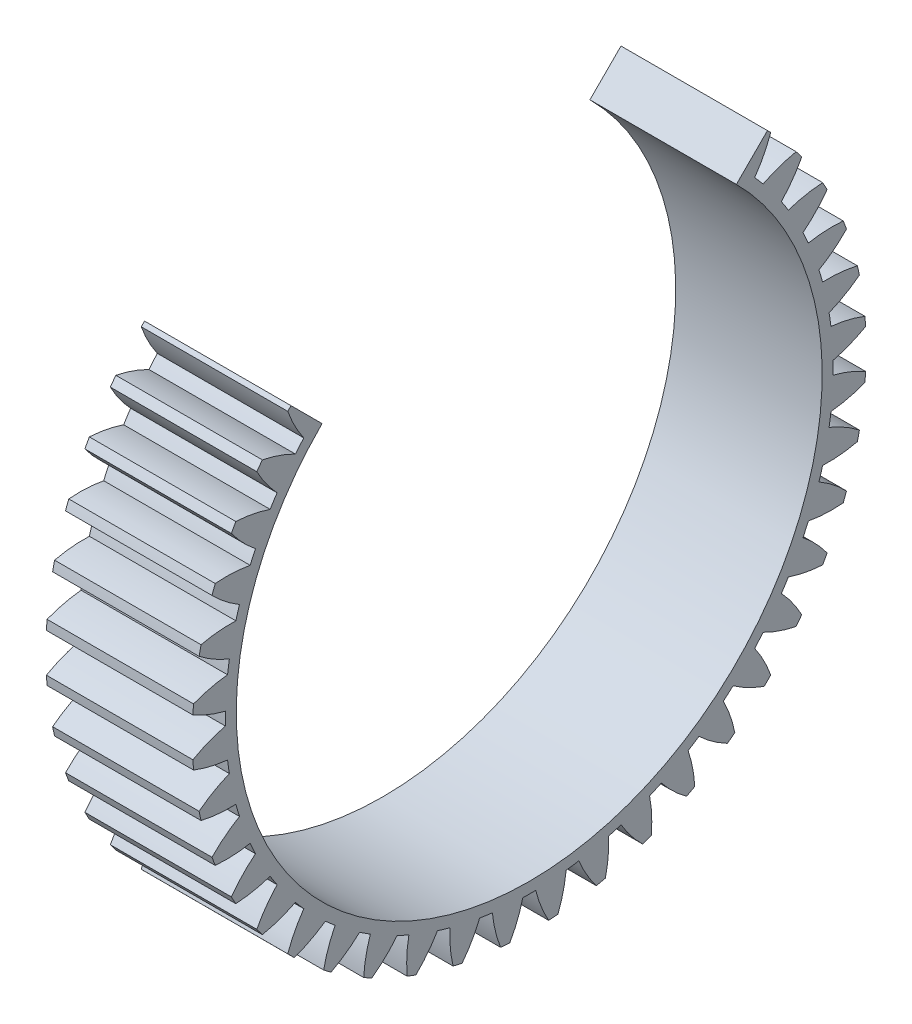
SolidWorks part; units mm, degrees
ref_plane "Plane1" through (0, 0, 0) normal (0, 0, 1) x (1, 0, 0)
ref_plane "Plane2" through (0, 0, 0) normal (0, 1, 0) x (1, 0, 0)
ref_plane "Plane3" through (0, 0, 0) normal (1, 0, 0) x (0, 0, -1)
other "Configuration Table"
sketch "HoldingSke" plane through (0, 0, 0) normal (0, 1, 0) x (1, 0, 0)
  line L0 (0, 0) -> (0.4796, -0.4631)
  line L1 (-15, 0) -> (100, 0) construction
  line L2 (0, 0) -> (-2.1039, 2.3779)
  line L3 (0, 0) -> (-11.863, 4.5341)
  line L4 (0, 0) -> (6.2122, 5.9991)
  line L5 (0, 0) -> (-46.8476, -17.4728)
  line L6 (0, 0) -> (-8.2896, -5.593)
  line L7 (-2.1039, 2.3779) -> (8.6586, 51.2059)
  line L8 (-76.2, 54.61) -> (-71.8, 54.61)
  line L9 (-71.009, 38.7566) -> (-53.1078, 45.2721)
  line L10 (-76.2, 71.12) -> (104.1128, 71.12)
  line L11 (0, 0) -> (-10, 0)
  line L12 (-76.2, 101.6) -> (-76.147, 101.6)
  line L13 (24.9733, 27.94) -> (52.9518, 28.4284)
  line L14 (24.9733, 27.94) -> (24.9743, 27.94)
  line L15 (24.9733, 27.94) -> (100.4006, 29.5858)
  line L16 (-63.627, -1.5) -> (-12.827, -1.5)
  circle A0 centre (0, 0) radius 30
  circle A1 centre (0, 0) radius 31.124
  circle A2 centre (0, 0) radius 37.5
  circle A3 centre (0, 0) radius 30
  dimension "MHD" = 62.248
  dimension "Hub_dia" = 75
  dimension "Bore" = 60
  dimension "MBD" = 60
  dimension "Num_teeth" = 44
  dimension "Pitch" = 0.6667
  dimension "Overall_len" = 50
  dimension "Show_teeth" = 44
  dimension "Thickness" = 10
  dimension "OAL" = 50.0001
  dimension "T_dim" = 4.4
  dimension "Ap" = 20
  dimension "H" = 19.05
  dimension "Pitch_radius" = 180.3128
  dimension "Width" = 10
  dimension "Backlash" = 0.053
  dimension "Addendum_fac" = 1
  dimension "Dedendum_fac" = 1.25
  dimension "Clearance_fac" = 0.25
  dimension "Dedendum_add" = 0.001
  dimension "Module" = 1.5
sketch "BasProSke" plane through (0, 0, 0) normal (0, 1, 0) x (1, 0, 0)
  line L0 (-10, 0) -> (60, 0) construction
  line L1 (0, 0) -> (0, 34.5)
  line L2 (0, 0) -> (15, 0)
  line L3 (15, 0) -> (15, 34.5)
  line L4 (15, 34.5) -> (0, 34.5)
  dimension "Thickness" = 15
  dimension "Diameter" = 69
revolve "Base-Revolve" add sketch "BasProSke" angle 360 about L0
sketch "TooCutSke" plane through (0, 0, 0) normal (1, 0, 0) x (0, 0, -1)
  line L1 (0, 0) -> (0, 107) construction
  line L2 (0, 0) -> (-1.2706, 32.9755) construction
  line L3 (0, 0) -> (-4.7058, 65.7962) construction
  line L4 (-1.2706, 32.9755) -> (-2.3529, 32.8981) construction
  arc A0 (0.6591, 31.117) -> (-0.6591, 31.117) centre (0, 0) ccw
  arc A1 (2.0005, 34.4674) -> (-2.0005, 34.4674) centre (0, 0) ccw
  circle A2 centre (0, 0) radius 33 construction
  circle A3 centre (0, 0) radius 31.0099 construction
  arc A4 (-0.6591, 31.117) -> (-2.0005, 34.4674) centre (-13.4691, 27.932) ccw
  arc A5 (2.0005, 34.4674) -> (0.6591, 31.117) centre (13.4691, 27.932) ccw
  dimension "Root_dia" = 62.248
  dimension "Overcut_dia" = 69.0508
  dimension "Pitch_dia" = 66
  dimension "Base_dia" = 62.0197
  dimension "Flank_rad" = 13.2
  dimension "Half_ang" = 4.091
  dimension "Half_CT" = 1.0851
extrude "ToothCut" cut sketch "TooCutSke" along normal through all
fillet "Breaks" [suppressed] radius 0.03
fillet "RootFillets" [suppressed] radius 0.376
pattern_circular "TeethCuts" count 44 every 8.182 about axis through (-10, 0, 0) along (1, 0, 0) of "ToothCut", "RootFillets", "Breaks"
sketch "HubNeaOneSke" plane through (0, 0, 0) normal (-1, 0, 0) x (0, 0, 1)
  circle A0 centre (0, 0) radius 31.124
  dimension "Diameter" = 62.248
extrude "HubNearOne" [suppressed] add sketch "HubNeaOneSke" along normal blind 35.0001
sketch "HubNeaBotSke" plane through (0, 0, 0) normal (-1, 0, 0) x (0, 0, 1)
  circle A0 centre (0, 0) radius 31.124
  dimension "Diameter" = 62.248
extrude "HubNearBoth" [suppressed] add sketch "HubNeaBotSke" along normal blind 17.5
ref_plane "FarPln" through (15, 0, 0) normal (1, 0, 0) x (0, 0, -1)
sketch "HubFarSke" plane through (15, 0, 0) normal (1, 0, 0) x (0, 0, -1)
  circle A0 centre (0, 0) radius 31.124
  dimension "Diameter" = 62.248
extrude "HubFar" [suppressed] add sketch "HubFarSke" along normal blind 17.5
sketch "BorSke" plane through (0, 0, 0) normal (1, 0, 0) x (0, 0, -1)
  circle A0 centre (0, 0) radius 30
  dimension "Diameter" = 60
extrude "Bore" cut sketch "BorSke" along normal mid plane 100.0001
sketch "KeySke" plane through (0, 0, 0) normal (1, 0, 0) x (0, 0, -1)
  line L0 (-9, 0) -> (-9, 34.4)
  line L1 (-9, 34.4) -> (9, 34.4)
  line L2 (9, 34.4) -> (9, 0)
  line L3 (0, 0) -> (0, 34) construction
  line L4 (-9, 0) -> (9, 0)
  dimension "Offset" = 34.4
  dimension "Width" = 18
extrude "Keyway" [suppressed] cut sketch "KeySke" along normal mid plane 100.0001
pattern_circular "Keyway2" [suppressed] count 2 every 90 about axis through (-10, 0, 0) along (1, 0, 0)
sketch "Sketch1" plane through (15, 0, 0) normal (1, 0, 0) x (0, 0, -1)
  line L0 (-24.3952, 24.3952) -> (-21.2132, 21.2132)
  line L1 (-21.2132, 21.2132) -> (0, 0) construction
  line L2 (0, 0) -> (21.2132, 21.2132) construction
  line L3 (24.3952, 24.3952) -> (21.2132, 21.2132)
  line L4 (0, 0) -> (0, 34.5) construction
  arc A0 (-24.3952, 24.3952) -> (24.3952, 24.3952) centre (0, 0) cw
  arc A1 (-21.2132, 21.2132) -> (21.2132, 21.2132) centre (0, 0) cw
  circle A2 centre (0, 0) radius 30 construction
  arc A3 (-1.9865, 34.4428) -> (-2.9355, 34.3749) centre (0, 0) ccw construction
  point P11 (-2.4612, 34.4121)
  dimension "D1" = 45
  dimension "D2" = 45
extrude "Cut-Extrude1" cut sketch "Sketch1" against normal through all
equation "' \"Module@HoldingSke\" = 6.35"
equation "' \"Num_teeth@HoldingSke\" = 12"
equation "' \"Ap@HoldingSke\" =  20"
equation "' \"Ap@HoldingSke\" = 20"
equation "' \"Width@HoldingSke\" = 0.5 * 25.4"
equation "' \"Hub_dia@HoldingSke\"= 1 * 25.4"
equation "' \"Hub_dia@HoldingSke\" = 1 * 25.4"
equation "' \"Overall_len@HoldingSke\" = 1.0 * 25.4"
equation "' \"Bore@HoldingSke\" = 0.75 * 25.4"
equation "' \"T_dim@HoldingSke\" = 0.1 * 25.4"
equation "' \"Width@KeySke\" = 0.25 * 25.4"
equation "' \"Show_teeth@HoldingSke\" = 13"
equation "' \"Backlash@HoldingSke\" = 0.009 * 25.4"
equation "' \"Addendum_fac@HoldingSke\" = 1.0"
equation "' \"Dedendum_fac@HoldingSke\" = 1.25"
equation "' \"Dedendum_add@HoldingSke\" = 0.00005 * 25.4"
equation "' \"Clearance_fac@HoldingSke\" = 0.25"
equation "\"Pitch@HoldingSke\" = 1 / \"Module@HoldingSke\""
equation "\"Overcut_dia@TooCutSke\" = (\"Num_teeth@HoldingSke\" + 2 * \"Addendum_fac@HoldingSke\") / \"Pitch@HoldingSke\" + 0.002 * 25.4"
equation "\"Pitch_dia@TooCutSke\" = \"Num_teeth@HoldingSke\" / \"Pitch@HoldingSke\""
equation "\"Base_dia@TooCutSke\" = \"Num_teeth@HoldingSke\" / \"Pitch@HoldingSke\" * cos((\"Ap@HoldingSke\"  * 3.14159265 / 180))"
equation "\"Root_dia@TooCutSke\" = (\"Num_teeth@HoldingSke\" + 2) / \"Pitch@HoldingSke\" - 2 * (\"Addendum_fac@HoldingSke\" + \"Dedendum_fac@HoldingSke\") / \"Pitch@HoldingSke\" - \"Dedendum_add@HoldingSke\" * 2"
equation "\"Half_ang@TooCutSke\" = 180 / \"Num_teeth@HoldingSke\""
equation "\"Half_CT@TooCutSke\" = \"Num_teeth@HoldingSke\" / \"Pitch@HoldingSke\" * sin((3.14159265 / 2 / \"Num_teeth@HoldingSke\")) / 2 - 7 * \"Backlash@HoldingSke\" / 4"
equation "\"Flank_rad@TooCutSke\" = \"Num_teeth@HoldingSke\" / \"Pitch@HoldingSke\" / 5"
equation "\"Radius@RootFillets\" = \"Clearance_fac@HoldingSke\" / \"Pitch@HoldingSke\" + \"Dedendum_add@HoldingSke\""
equation "\"Break_rad@Breaks\" = 0.02 / \"Pitch@HoldingSke\""
equation "\"Thickness@HoldingSke\" = \"Width@HoldingSke\""
equation "\"OAL@HoldingSke\" = \"Thickness@HoldingSke\""
equation "\"MHD@HoldingSke\" = (\"Num_teeth@HoldingSke\" + 2) / \"Pitch@HoldingSke\" - 2 * (\"Addendum_fac@HoldingSke\" + \"Dedendum_fac@HoldingSke\")  / \"Pitch@HoldingSke\" - \"Dedendum_add@HoldingSke\" * 2"
equation "\"MBD@HoldingSke\" = (\"Num_teeth@HoldingSke\" + 2) / \"Pitch@HoldingSke\" - 2 * (\"Addendum_fac@HoldingSke\" + \"Dedendum_fac@HoldingSke\")  / \"Pitch@HoldingSke\" - \"Dedendum_add@HoldingSke\" * 2 - 0.002 * 25.4"
equation "\"MHD@HoldingSke\" = ((sgn( \"MHD@HoldingSke\" - \"Hub_dia@HoldingSke\" )-1)*( \"MHD@HoldingSke\" - \"Hub_dia@HoldingSke\" ))/-2+ \"Hub_dia@HoldingSke\""
equation "\"MBD@HoldingSke\" = ((sgn( \"MBD@HoldingSke\" - \"Bore@HoldingSke\" )-1)*( \"MBD@HoldingSke\" - \"Bore@HoldingSke\" ))/-2+ \"Bore@HoldingSke\""
equation "\"OAL@HoldingSke\" = ((sgn( \"OAL@HoldingSke\" - \"Overall_len@HoldingSke\" )+1)*( \"OAL@HoldingSke\" - \"Overall_len@HoldingSke\" ))/2 + \"Overall_len@HoldingSke\" + 0.000002 * 25.4"
equation "\"Num_teeth@TeethCuts\" = int( \"Show_teeth@HoldingSke\" ) + 1"
equation "\"Num_teeth@TeethCuts\" = ((sgn( \"Num_teeth@TeethCuts\" - \"Num_teeth@HoldingSke\" )-1)*( \"Num_teeth@TeethCuts\" - \"Num_teeth@HoldingSke\" ))/-2+ \"Num_teeth@HoldingSke\""
equation "\"Num_teeth@TeethCuts\" = ((sgn( \"Num_teeth@TeethCuts\" - 2.0)+1)*( \"Num_teeth@TeethCuts\" - 2.0))/2 +2.0"
equation "\"Angle@TeethCuts\" = 360.0 / \"Num_teeth@HoldingSke\""
equation "\"Diameter@BasProSke\" = (\"Num_teeth@HoldingSke\" + 2 * \"Addendum_fac@HoldingSke\") / \"Pitch@HoldingSke\""
equation "' \"Fillet_rad@BasProSke\" =  \"Thickness@HoldingSke\" * 0.05"
equation "' \"Fillet_rad@BasProSke\" = \"Thickness@HoldingSke\" * 0.05"
equation "\"MHD@HoldingSke\" = ((sgn( \"MHD@HoldingSke\" - \"Root_dia@TooCutSke\" )-1)*( \"MHD@HoldingSke\" - \"Root_dia@TooCutSke\" ))/-2+ \"Root_dia@TooCutSke\""
equation "\"Diameter@HubNeaOneSke\" = \"MHD@HoldingSke\""
equation "\"Length@HubNearOne\" = \"OAL@HoldingSke\" - \"Thickness@BasProSke\""
equation "\"Diameter@HubNeaBotSke\" = \"MHD@HoldingSke\""
equation "\"Length@HubNearBoth\" = ( \"OAL@HoldingSke\" - \"Thickness@BasProSke\" ) / 2.0"
equation "\"Thickness@FarPln\" = \"Thickness@BasProSke\""
equation "\"Diameter@HubFarSke\" = \"MHD@HoldingSke\""
equation "\"Length@HubFar\" = ( \"OAL@HoldingSke\" - \"Thickness@BasProSke\" ) / 2.0"
equation "\"Diameter@BorSke\" = \"MBD@HoldingSke\""
equation "\"D1@Bore\" = \"OAL@HoldingSke\" * 2.0"
equation "\"D1@Keyway\" = \"OAL@HoldingSke\" * 2.0"
equation "\"Offset@KeySke\" = \"T_dim@HoldingSke\" + \"MBD@HoldingSke\" / 2.0"
